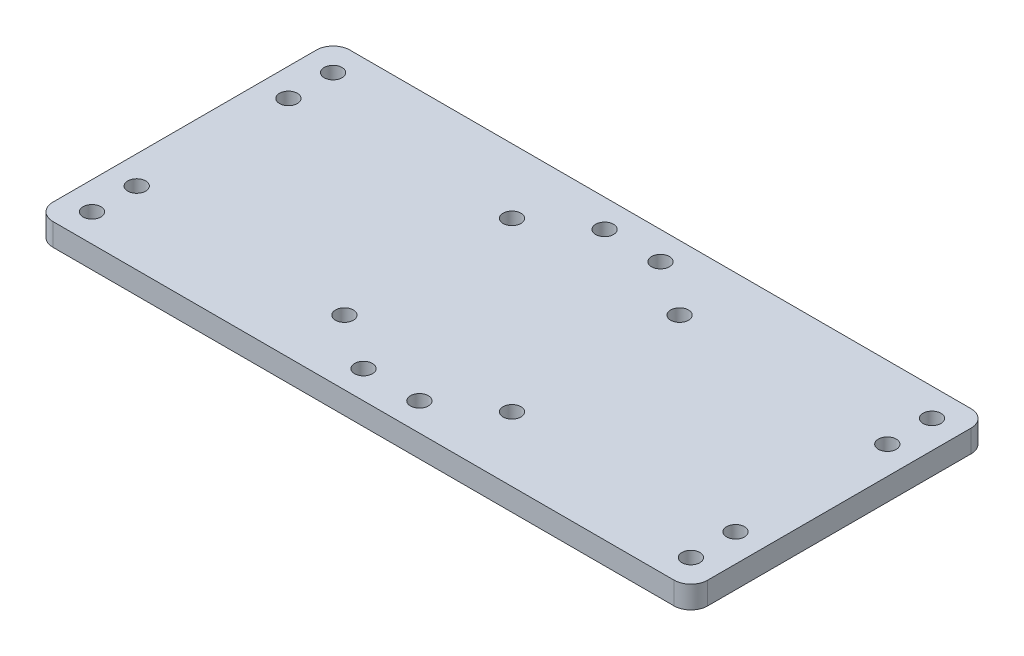
SolidWorks part; units mm, degrees
ref_plane "前视基准面" through (0, 0, 0) normal (0, 0, 1) x (1, 0, 0)
ref_plane "上视基准面" through (0, 0, 0) normal (0, 1, 0) x (1, 0, 0)
ref_plane "右视基准面" through (0, 0, 0) normal (1, 0, 0) x (0, 0, -1)
sketch "草图1" plane through (0, 0, 0) normal (0, 1, 0) x (1, 0, 0)
  line L1 (-58.6, 26.5803) -> (58.6, 26.5803)
  line L2 (-58.6, 26.5803) -> (-58.6, -26.5803)
  line L3 (-58.6, -26.5803) -> (58.6, -26.5803)
  line L4 (58.6, 26.5803) -> (58.6, -26.5803)
  line L5 (-58.6, 26.5803) -> (58.6, -26.5803) construction
  line L6 (-58.6, -26.5803) -> (58.6, 26.5803) construction
  point P0 (0, 0)
  dimension "D1" = 117.2
  dimension "D2" = 53.1606
extrude "凸台-拉伸1" add sketch "草图1" along normal blind 4
sketch "草图2" plane through (0, 4, 0) normal (0, 1, 0) x (1, 0, 0)
  line L0 (-58.6, 0) -> (58.6, 0) construction
  line L1 (-58.6, 26.5803) -> (-58.6, -26.5803) construction
  line L2 (58.6, -26.5803) -> (58.6, 26.5803) construction
  line L3 (0, -26.5803) -> (0, 26.5803) construction
  line L4 (-58.6, -26.5803) -> (58.6, -26.5803) construction
  line L5 (58.6, 26.5803) -> (-58.6, 26.5803) construction
sketch "草图3" plane through (0, 4, 0) normal (0, 1, 0) x (1, 0, 0)
  line L0 (-58.6, -26.5803) -> (58.6, -26.5803) construction
  line L1 (-58.6, 26.5803) -> (-58.6, -26.5803) construction
  line L2 (0, -26.5803) -> (0, 26.5803) construction
  line L3 (0, 26.5803) -> (0, -26.5803) construction
  line L4 (58.6, 0) -> (-58.6, 0) construction
  circle A0 centre (-53.6, -21.5803) radius 1.6
  circle A1 centre (-53.6, -13.5803) radius 1.6
  circle A2 centre (-5, -21.5803) radius 1.6
  circle A3 centre (5, -21.5803) radius 1.6
  circle A4 centre (53.6, -13.5803) radius 1.6
  circle A5 centre (53.6, -21.5803) radius 1.6
  circle A6 centre (-53.6, 13.5803) radius 1.6
  circle A7 centre (-53.6, 21.5803) radius 1.6
  circle A8 centre (-5, 21.5803) radius 1.6
  circle A9 centre (5, 21.5803) radius 1.6
  circle A10 centre (53.6, 21.5803) radius 1.6
  circle A11 centre (53.6, 13.5803) radius 1.6
  dimension "D1" = 8
  dimension "D2" = 5
  dimension "D3" = 5
  dimension "D4" = 5
  dimension "D5" = 5
  dimension "D6" = 3.2
extrude "切除-拉伸1" cut sketch "草图3" against normal blind 4
fillet "圆角1" radius 3 4 edges at (58.6, 2, 26.5803) (-58.6, 2, -26.5803) (58.6, 2, -26.5803) (-58.6, 2, 26.5803)
sketch "草图4" plane through (0, 4, 0) normal (0, 1, 0) x (1, 0, 0)
  line L0 (-20, 0) -> (20, 0) construction
  line L5 (-20, 20) -> (20, -20) construction
  line L6 (-20, -20) -> (20, 20) construction
  circle A0 centre (-15, -15) radius 1.6
  circle A1 centre (15, 15) radius 1.6
  circle A2 centre (15, -15) radius 1.6
  circle A3 centre (-15, 15) radius 1.6
  circle A4 centre (53.6, 21.5803) radius 1.6 construction
  point P0 (0, 0)
  dimension "D3" = 3.2
  dimension "D4" = 38.6
  dimension "D1" = 40
  dimension "D2" = 40
  dimension "D5" = 68.6
  dimension "D6" = 6.5803
extrude "切除-拉伸2" cut sketch "草图4" against normal blind 10
